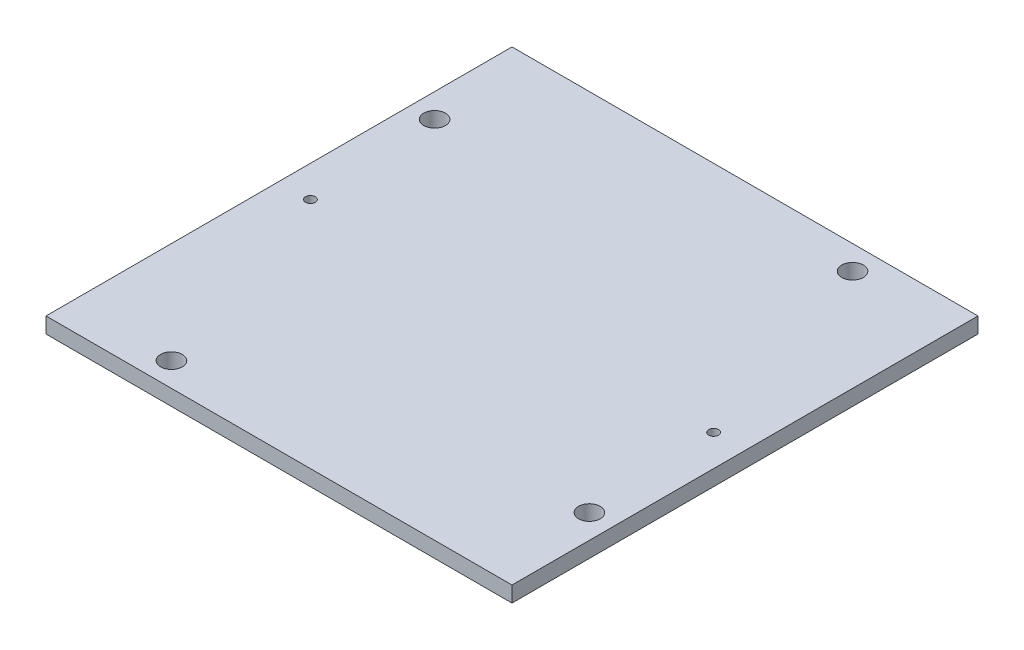
SolidWorks part; units mm, degrees
ref_plane "Front" through (0, 0, 0) normal (0, 0, 1) x (1, 0, 0)
ref_plane "Top" through (0, 0, 0) normal (0, 1, 0) x (1, 0, 0)
ref_plane "Right" through (0, 0, 0) normal (1, 0, 0) x (0, 0, -1)
sketch "Sketch1" plane through (0, 0, 0) normal (0, 1, 0) x (1, 0, 0)
  line L1 (-23.7744, 23.7744) -> (23.7744, 23.7744)
  line L2 (-23.7744, 23.7744) -> (-23.7744, -23.7744)
  line L3 (-23.7744, -23.7744) -> (23.7744, -23.7744)
  line L4 (23.7744, 23.7744) -> (23.7744, -23.7744)
  line L5 (-23.7744, 23.7744) -> (23.7744, -23.7744) construction
  line L6 (-23.7744, -23.7744) -> (23.7744, 23.7744) construction
  point P0 (0, 0)
  dimension "D1" = 47.5488
  dimension "D2" = 47.5488
extrude "Boss-Extrude1" add sketch "Sketch1" along normal blind 1.6002
sketch "Sketch2" plane through (0, 1.6002, 0) normal (0, 1, 0) x (1, 0, 0)
  line L0 (0, 20) -> (0, -20)
  line L1 (-20, 20) -> (20, 20)
  line L2 (-20, 20) -> (-20, -20)
  line L3 (-20, -20) -> (20, -20)
  line L4 (20, 20) -> (20, -20)
  line L5 (-20, 20) -> (20, -20) construction
  line L6 (-20, -20) -> (20, 20) construction
  line L7 (-20, 0) -> (20, 0)
  point P0 (0, 0)
  dimension "D1" = 40
  dimension "D3" = 40
sketch "Sketch3" plane through (0, 1.6002, 0) normal (0, 1, 0) x (1, 0, 0)
  line L0 (0, 0) -> (20.574, 0)
  line L2 (0, 0) -> (-20.574, 0)
  line L5 (23.7744, 23.7744) -> (-23.7744, 23.7744) construction
  line L6 (-23.7744, -23.7744) -> (23.7744, -23.7744) construction
  line L9 (-23.7744, 23.7744) -> (-23.7744, -23.7744) construction
  line L10 (23.7744, -23.7744) -> (23.7744, 23.7744) construction
  line L12 (-23.7744, 23.7744) -> (23.7744, 23.7744)
  line L13 (-23.7744, 23.7744) -> (-23.7744, -23.7744)
  line L14 (-23.7744, -23.7744) -> (23.7744, -23.7744)
  line L15 (23.7744, 23.7744) -> (23.7744, -23.7744)
  line L16 (-23.7744, 23.7744) -> (23.7744, -23.7744) construction
  line L17 (-23.7744, -23.7744) -> (23.7744, 23.7744) construction
  circle A0 centre (-20.574, 0) radius 0.5
  circle A1 centre (20.574, 0) radius 0.5
  circle A2 centre (21.3233, -13.4239) radius 1.1049
  circle A3 centre (-13.4239, -21.3233) radius 1.1049
  circle A4 centre (-21.3233, 13.4239) radius 1.1049
  circle A5 centre (13.4239, 21.3233) radius 1.1049
  dimension "D1" = 1
  dimension "D2" = 1
  dimension "D3" = 2.2098
  dimension "D6" = 2.2098
  dimension "D8" = 2.2098
  dimension "D10" = 2.2098
  dimension "D4" = 10.3505
  dimension "D5" = 2.4511
  dimension "D7" = 10.3505
  dimension "D9" = 2.4511
  dimension "D11" = 20.574
  dimension "D12" = 20.574
  dimension "D13" = 2.4511
  dimension "D14" = 2.4511
  dimension "D15" = 10.3505
  dimension "D16" = 10.3505
extrude "Cut-Extrude1" cut sketch "Sketch3" against normal blind 1.6002 contours A0 | A1 | A3 | A2 | A5 | A4
